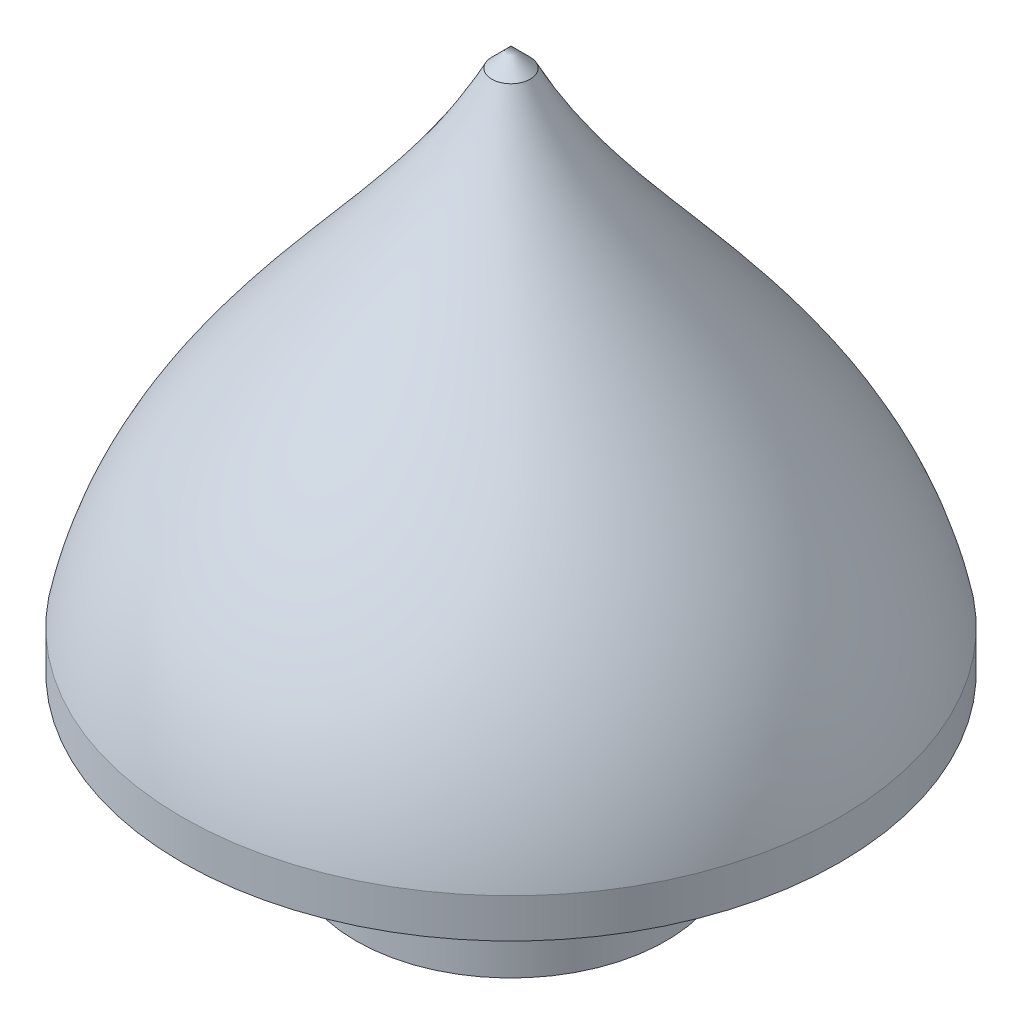
SolidWorks part; units mm, degrees
ref_plane "Front Plane" through (0, 0, 0) normal (0, 0, 1) x (1, 0, 0)
ref_plane "Top Plane" through (0, 0, 0) normal (0, 1, 0) x (1, 0, 0)
ref_plane "Right Plane" through (0, 0, 0) normal (1, 0, 0) x (0, 0, -1)
sketch "Sketch1" plane through (0, 0, 0) normal (0, 0, 1) x (1, 0, 0)
  line L0 (0, 0) -> (0, -2) construction
  line L1 (0, 0) -> (0, 7) construction
  line L2 (0, -2) -> (-2, -2)
  line L3 (-2, -2) -> (-2, 0)
  line L4 (-2, 0) -> (-4.2443, 0)
  line L5 (-4.2443, 0) -> (-4.2443, 0.5063)
  line L6 (0, 7) -> (-0.2474, 6.7526)
  line L7 (0, -2) -> (0, 7)
  spline S0 degree 3 poles (-0.2474, 6.7526) (-1.3773, 4.5151) (-3.6973, 3.0819) (-4.2443, 0.5063) knots 0 0 0 0 1 1 1 1
  dimension "D1" = 2
  dimension "D2" = 7
  dimension "D3" = 2
revolve "Revolve1" add sketch "Sketch1" angle 360 about L7
